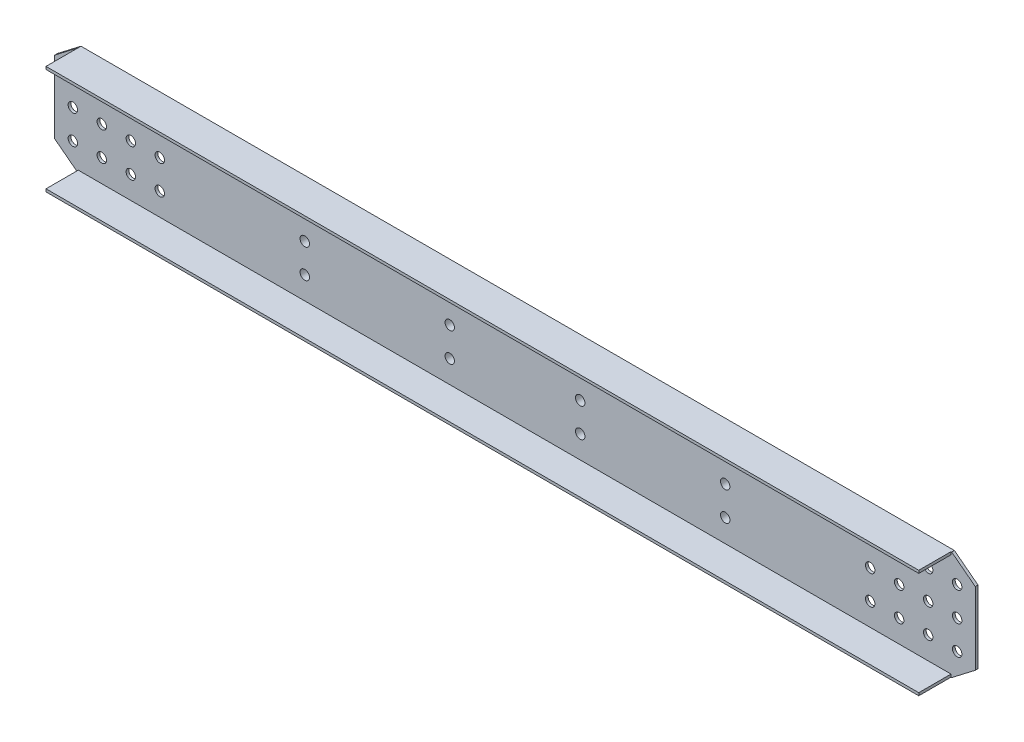
SolidWorks part; units mm, degrees
ref_plane "前视" through (0, 0, 0) normal (0, 0, 1) x (1, 0, 0)
ref_plane "上视" through (0, 0, 0) normal (0, 1, 0) x (1, 0, 0)
ref_plane "右视" through (0, 0, 0) normal (1, 0, 0) x (0, 0, -1)
sketch "草图1" plane through (0, 0, 0) normal (0, 0, 1) x (1, 0, 0)
  line L0 (0, -30.9807) -> (0, 402.9291) construction
  line L1 (-1205, 0) -> (1205, 0)
  line L2 (-1270, 50) -> (-1270, 250)
  line L3 (-1205, 300) -> (1205, 300)
  line L4 (-1270, 50) -> (-1205, 0)
  line L5 (-1270, 250) -> (-1205, 300)
  line L6 (-1329.5124, 150) -> (23.7415, 150) construction
  line L7 (-1307.9834, 230) -> (-31.6189, 230) construction
  line L8 (-1220, -101.4655) -> (-1220, 369.0978) construction
  line L9 (1270, 250) -> (1205, 300)
  line L10 (-1140, 369.0978) -> (-1140, -101.4655) construction
  line L11 (1270, 50) -> (1205, 0)
  line L12 (-1060, -101.4655) -> (-1060, 369.0978) construction
  line L13 (1270, 50) -> (1270, 250)
  line L14 (-980, 369.0978) -> (-980, -101.4655) construction
  circle A0 centre (-1220, 230) radius 13
  circle A1 centre (-1220, 150) radius 13
  circle A2 centre (-1140, 230) radius 13
  circle A3 centre (-1140, 150) radius 13
  circle A4 centre (-1060, 230) radius 13
  circle A5 centre (-1060, 150) radius 13
  circle A6 centre (-980, 150) radius 13
  circle A7 centre (-1060, 70) radius 13
  circle A8 centre (-1140, 70) radius 13
  circle A9 centre (-1220, 70) radius 13
  circle A10 centre (1220, 70) radius 13
  circle A11 centre (1140, 70) radius 13
  circle A12 centre (1060, 70) radius 13
  circle A13 centre (980, 150) radius 13
  circle A14 centre (1060, 150) radius 13
  circle A15 centre (1060, 230) radius 13
  circle A16 centre (1140, 150) radius 13
  circle A17 centre (1140, 230) radius 13
  circle A18 centre (1220, 150) radius 13
  circle A19 centre (1220, 230) radius 13
  circle A20 centre (-980, 70) radius 13
  circle A21 centre (-980, 230) radius 13
  circle A22 centre (980, 70) radius 13
  circle A23 centre (980, 230) radius 13
  point P8 (0, 300)
  point P65 (0, 0)
  dimension "D13" = 26
  dimension "D14" = 26
  dimension "D1" = 1205
  dimension "D2" = 300
  dimension "D3" = 65
  dimension "D4" = 65
  dimension "D5" = 50
  dimension "D6" = 50
  dimension "D7" = 70
  dimension "D8" = 80
  dimension "D9" = 50
  dimension "D10" = 80
  dimension "D11" = 80
  dimension "D12" = 80
  dimension "D15" = 70
  dimension "D16" = 70
extrude "基体-拉伸" add sketch "草图1" against normal blind 7.5
sketch "草图2" plane through (0, 0, 0) normal (0, 0, 1) x (1, 0, 0)
  line L0 (-1399.9508, 150) -> (-832.4876, 150) construction
  line L1 (-1205, 300) -> (1203.049, 300)
  line L2 (-1205, 300) -> (-1205, 292.5)
  line L3 (-1205, 292.5) -> (1203.049, 292.5)
  line L4 (1203.049, 300) -> (1203.049, 292.5)
  line L5 (-1205, 0) -> (1205, 0) construction
  line L6 (1203.049, 0) -> (1203.049, 7.5)
  line L7 (-1205, 7.5) -> (1203.049, 7.5)
  line L8 (-1205, 0) -> (-1205, 7.5)
  line L9 (-1205, 0) -> (1203.049, 0)
  dimension "D1" = 7.5
extrude "凸台-拉伸1" add sketch "草图2" along normal blind 89
sketch "草图3" plane through (0, 0, -7.5) normal (0, 0, -1) x (-1, 0, 0)
  line L0 (0, -46.5184) -> (0, 412.0245) construction
  line L1 (-180, 412.0245) -> (-180, -46.5184) construction
  line L2 (-580, 412.0245) -> (-580, -73.5011) construction
  line L3 (-1205, 300) -> (1205, 300) construction
  line L4 (-620, 270) -> (-540, 270)
  line L5 (-620, 270) -> (-620, 30)
  line L6 (-620, 30) -> (-540, 30)
  line L7 (-540, 270) -> (-540, 30)
  line L8 (-220, 270) -> (-140, 270)
  line L9 (-220, 270) -> (-220, 30)
  line L10 (-220, 30) -> (-140, 30)
  line L11 (-140, 270) -> (-140, 30)
  line L12 (140, 270) -> (140, 30)
  line L13 (220, 30) -> (140, 30)
  line L14 (220, 270) -> (220, 30)
  line L15 (220, 270) -> (140, 270)
  line L16 (540, 270) -> (540, 30)
  line L17 (620, 30) -> (540, 30)
  line L18 (620, 270) -> (620, 30)
  line L19 (620, 270) -> (540, 270)
  dimension "D1" = 180
  dimension "D2" = 400
  dimension "D3" = 240
  dimension "D4" = 30
  dimension "D5" = 80
  dimension "D6" = 80
extrude "凸台-拉伸2" add sketch "草图3" along normal blind 16
sketch "草图4" plane through (0, 0, 0) normal (0, 0, 1) x (1, 0, 0)
  line L0 (0, -259.4133) -> (0, 624.9194) construction
  line L1 (-180, -162.9649) -> (-180, 487.5033) construction
  line L2 (1203.049, 300) -> (-1205, 300) construction
  line L3 (-580, 487.5033) -> (-580, -162.9649) construction
  line L4 (-781.6864, 230) -> (-55.0372, 230) construction
  line L6 (-55.0372, 150) -> (-781.6864, 150) construction
  line L8 (-781.6864, 70) -> (-55.0372, 70) construction
  circle A0 centre (-580, 230) radius 13
  circle A1 centre (-580, 150) radius 13
  circle A2 centre (-180, 230) radius 13
  circle A3 centre (-180, 150) radius 13
  circle A4 centre (-180, 70) radius 13
  circle A5 centre (-580, 70) radius 13
  circle A6 centre (580, 70) radius 13
  circle A7 centre (180, 70) radius 13
  circle A8 centre (180, 150) radius 13
  circle A9 centre (180, 230) radius 13
  circle A10 centre (580, 150) radius 13
  circle A11 centre (580, 230) radius 13
  dimension "D6" = 26
  dimension "D1" = 180
  dimension "D2" = 400
  dimension "D3" = 70
  dimension "D4" = 80
  dimension "D5" = 80
extrude "切除-拉伸1" cut sketch "草图4" against normal through all
